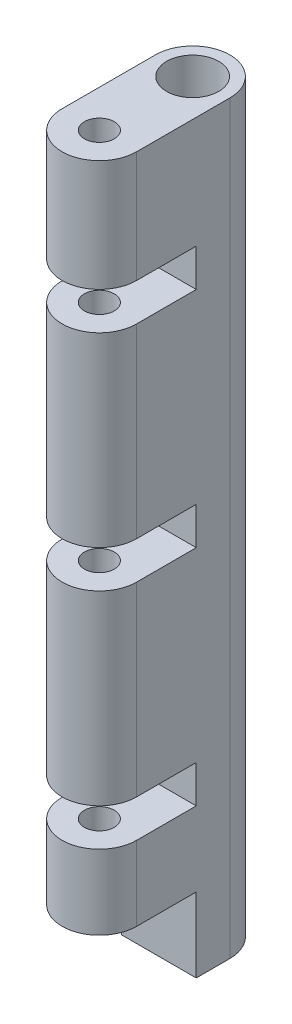
SolidWorks part; units mm, degrees
ref_plane "Front Plane" through (0, 0, 0) normal (0, 0, 1) x (1, 0, 0)
ref_plane "Top Plane" through (0, 0, 0) normal (0, 1, 0) x (1, 0, 0)
ref_plane "Right Plane" through (0, 0, 0) normal (1, 0, 0) x (0, 0, -1)
sketch "Sketch2" plane through (0, 0, 0) normal (0, 1, 0) x (1, 0, 0)
  circle A0 centre (0, 0) radius 4.445
  circle A1 centre (0, 0) radius 6.35
  dimension "D1" = 8.89
  dimension "D2" = 12.7
extrude "Boss-Extrude1" add sketch "Sketch2" along normal blind 127
sketch "Sketch3" plane through (0, 127, 0) normal (0, 1, 0) x (1, 0, 0)
  line L0 (-6.35, 0) -> (-6.35, -15.8981)
  line L1 (6.35, 0) -> (6.35, -15.8981)
  arc A0 (-6.35, -15.8981) -> (6.35, -15.8981) centre (0, -15.8981) ccw
  circle A1 centre (0, 0) radius 6.35 construction
  arc A2 (-6.35, 0) -> (6.35, 0) centre (0, 0) ccw
  circle A3 centre (0, -15.8981) radius 2.54
  dimension "D1" = 12.7
  dimension "D2" = 5.08
extrude "Boss-Extrude2" add sketch "Sketch3" against normal up to surface (127 mm away) up to face at (0, 0, 6.35)
sketch "Sketch4" plane through (6.35, 0, 0) normal (1, 0, 0) x (0, 0, -1)
  line L1 (-37.4881, 31.8008) -> (-5.7381, 31.8008)
  line L2 (-37.4881, 31.8008) -> (-37.4881, 25.4)
  line L3 (-37.4881, 25.4) -> (-5.7381, 25.4)
  line L4 (-5.7381, 31.8008) -> (-5.7381, 25.4)
  line L5 (0, 0) -> (-15.8981, 0) construction
  line L6 (-15.8981, 0) -> (-15.8981, 127) construction
  line L7 (-37.4591, 48.2005) -> (12.6646, 48.2005) construction
  line L8 (-37.4881, 69.9008) -> (-37.4881, 63.5)
  line L9 (-37.4881, 69.9008) -> (-5.7381, 69.9008)
  line L10 (-5.7381, 69.9008) -> (-5.7381, 63.5)
  line L11 (-37.4881, 63.5) -> (-5.7381, 63.5)
  line L12 (-37.4881, 108.0008) -> (-37.4881, 101.6)
  line L13 (-37.4881, 108.0008) -> (-5.7381, 108.0008)
  line L14 (-5.7381, 108.0008) -> (-5.7381, 101.6)
  line L15 (-37.4881, 101.6) -> (-5.7381, 101.6)
  line L17 (-5.7381, 0) -> (-37.4881, 0)
  line L18 (-5.7381, 0) -> (-5.7381, 12.7)
  line L19 (-5.7381, 12.7) -> (-37.4881, 12.7)
  line L20 (-37.4881, 0) -> (-37.4881, 12.7)
  point P10 (-5.7381, 28.6004)
  dimension "D1" = 10.16
  dimension "D2" = 25.4
  dimension "D3" = 6.4008
  dimension "D4" = 31.75
  dimension "D6" = 12.7
  dimension "D7" = 31.75
  dimension "D5" = 3
extrude "Cut-Extrude1" cut sketch "Sketch4" against normal blind 127
